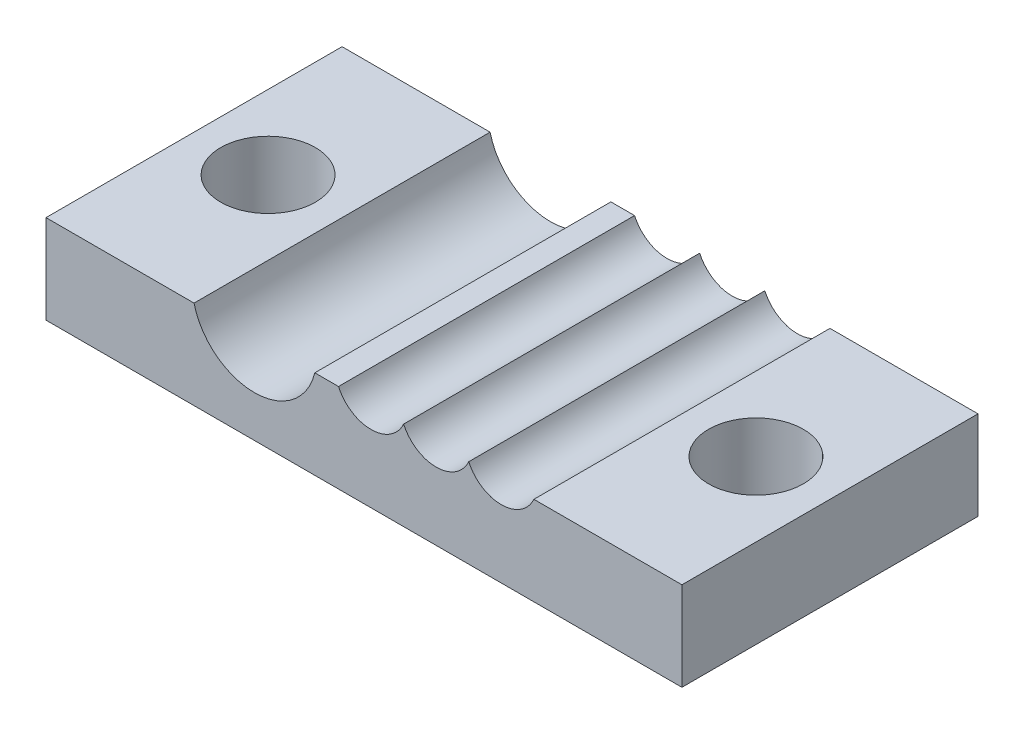
SolidWorks part; units mm, degrees
ref_plane "Front Plane" through (0, 0, 0) normal (0, 0, 1) x (1, 0, 0)
ref_plane "Top Plane" through (0, 0, 0) normal (0, 1, 0) x (1, 0, 0)
ref_plane "Right Plane" through (0, 0, 0) normal (1, 0, 0) x (0, 0, -1)
sketch "Sketch1" plane through (0, 0, 0) normal (0, 0, 1) x (1, 0, 0)
  line L0 (0, 0) -> (21.4792, 0)
  line L1 (21.4792, 0) -> (21.4792, 3)
  line L2 (0, 0) -> (0, 3)
  line L3 (10.9792, 3.5) -> (15.3792, 3.5) construction
  line L4 (0, 3) -> (5, 3)
  line L5 (9.0792, 3) -> (9.8792, 3)
  line L6 (7.0396, 3.5) -> (10.9792, 3.5) construction
  line L7 (16.4792, 3) -> (21.4792, 3)
  circle A0 centre (7.0396, 3.5) radius 2.3 construction
  circle A1 centre (10.9792, 3.5) radius 1.4083 construction
  circle A2 centre (13.1792, 3.5) radius 1.4083 construction
  circle A3 centre (15.3792, 3.5) radius 1.4083 construction
  arc A4 (5, 3) -> (9.0792, 3) centre (7.0396, 3.5) ccw
  arc A5 (9.8792, 3) -> (12.0792, 3) centre (10.9792, 3.5) ccw
  arc A6 (12.0792, 3) -> (14.2792, 3) centre (13.1792, 3.5) ccw
  arc A7 (14.2792, 3) -> (16.4792, 3) centre (15.3792, 3.5) ccw
  dimension "D1" = 4.6
  dimension "D2" = 4.4
  dimension "D3" = 0.2
  dimension "D4" = 0.2
  dimension "D5" = 0.5
  dimension "D6" = 0.8
  dimension "D7" = 5
  dimension "D8" = 3
extrude "Boss-Extrude1" add sketch "Sketch1" along normal blind 10
sketch "Sketch2" plane through (0, 0, 0) normal (0, -1, 0) x (1, 0, 0)
  line L0 (0, 5) -> (21.4792, 5) construction
  line L1 (0, 10) -> (0, 0) construction
  line L2 (21.4792, 10) -> (21.4792, 0) construction
  line L3 (2.5, 0) -> (2.5, 5) construction
  line L4 (5, 0) -> (0, 0) construction
  line L5 (18.9792, 0) -> (18.9792, 5) construction
  line L6 (21.4792, 0) -> (16.4792, 0) construction
  circle A0 centre (2.5, 5) radius 1.6
  circle A1 centre (18.9792, 5) radius 1.6
  dimension "D1" = 3.2
extrude "Cut-Extrude1" cut sketch "Sketch2" against normal through all
